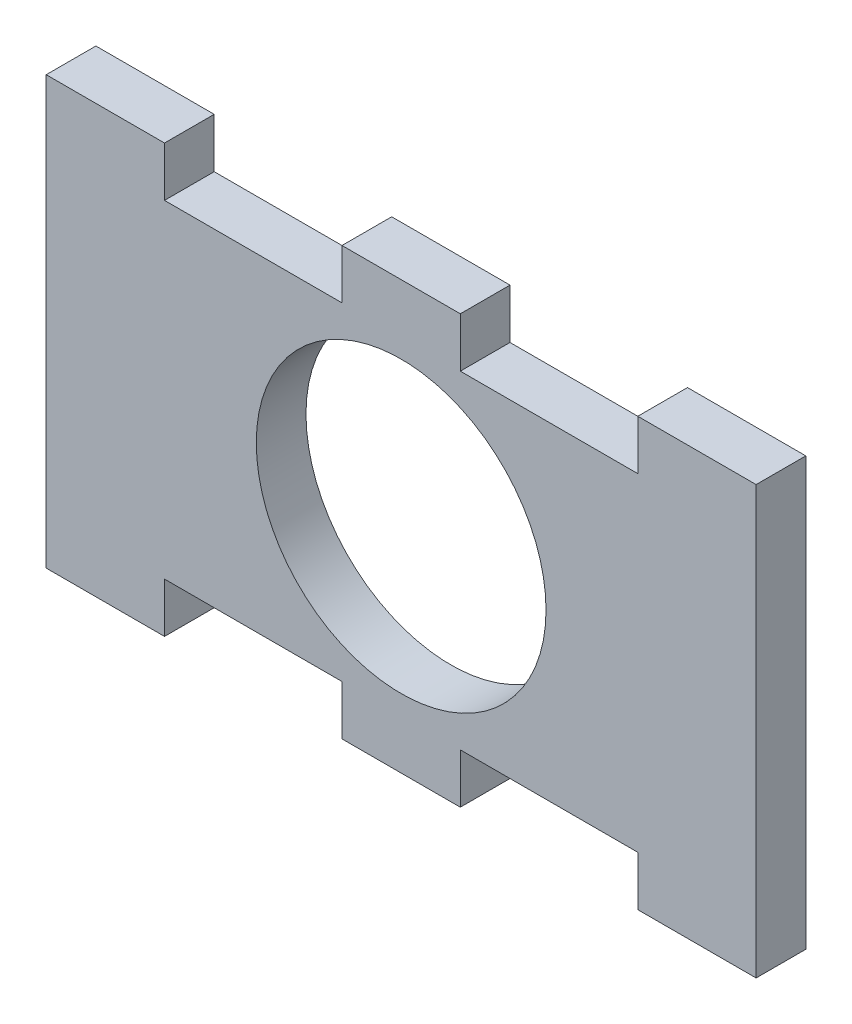
SolidWorks part; units mm, degrees
ref_plane "Front Plane" through (0, 0, 0) normal (0, 0, 1) x (1, 0, 0)
ref_plane "Top Plane" through (0, 0, 0) normal (0, 1, 0) x (1, 0, 0)
ref_plane "Right Plane" through (0, 0, 0) normal (1, 0, 0) x (0, 0, -1)
sketch "Sketch1" plane through (0, 0, 0) normal (0, 0, 1) x (1, 0, 0)
  line L1 (-38.1, 17.6) -> (38.1, 17.6)
  line L2 (-38.1, 17.6) -> (-38.1, -17.6)
  line L3 (-38.1, -17.6) -> (38.1, -17.6)
  line L4 (38.1, 17.6) -> (38.1, -17.6)
  line L5 (-38.1, 17.6) -> (38.1, -17.6) construction
  line L6 (-38.1, -17.6) -> (38.1, 17.6) construction
  point P0 (0, 0)
  dimension "D1" = 35.2
  dimension "D2" = 76.2
extrude "Boss-Extrude1" add sketch "Sketch1" against normal blind 5.334
sketch "Sketch2" plane through (0, 0, 0) normal (0, 0, 1) x (1, 0, 0)
  circle A0 centre (0, 0) radius 15.55
  dimension "D1" = 31.1
extrude "Cut-Extrude1" cut sketch "Sketch2" against normal through all
sketch "Sketch3" plane through (0, 17.6, 0) normal (0, 1, 0) x (1, 0, 0)
  line L0 (0, 14.0499) -> (0, 5.334) construction
  line L1 (38.1, 0) -> (-38.1, 0) construction
  line L2 (-38.1, 5.334) -> (-25.4, 5.334)
  line L3 (-38.1, 5.334) -> (-38.1, 0)
  line L4 (-38.1, 0) -> (-25.4, 0)
  line L5 (-25.4, 5.334) -> (-25.4, 0)
  line L6 (38.1, 5.334) -> (-38.1, 5.334) construction
  line L7 (6.35, 5.334) -> (-6.35, 5.334)
  line L8 (6.35, 5.334) -> (6.35, 0)
  line L9 (6.35, 0) -> (-6.35, 0)
  line L10 (-6.35, 5.334) -> (-6.35, 0)
  line L11 (0, 0) -> (0, -7.65) construction
  line L12 (25.4, 5.334) -> (25.4, 0)
  line L13 (38.1, 0) -> (25.4, 0)
  line L14 (38.1, 5.334) -> (38.1, 0)
  line L15 (38.1, 5.334) -> (25.4, 5.334)
  dimension "D1" = 12.7
  dimension "D2" = 6.35
extrude "Boss-Extrude2" add sketch "Sketch3" along normal blind 5.334
sketch "Sketch4" plane through (0, -17.6, 0) normal (0, -1, 0) x (1, 0, 0)
  line L0 (-38.1, -5.334) -> (38.1, -5.334) construction
  line L1 (-38.1, 0) -> (-25.4, 0)
  line L2 (-38.1, 0) -> (-38.1, -5.334)
  line L3 (-38.1, -5.334) -> (-25.4, -5.334)
  line L4 (-25.4, 0) -> (-25.4, -5.334)
  line L5 (0, 7.8784) -> (0, 0) construction
  line L6 (0, -5.334) -> (0, -11.385) construction
  line L7 (6.35, 0) -> (-6.35, 0)
  line L8 (6.35, 0) -> (6.35, -5.334)
  line L9 (6.35, -5.334) -> (-6.35, -5.334)
  line L10 (-6.35, 0) -> (-6.35, -5.334)
  line L11 (25.4, 0) -> (25.4, -5.334)
  line L12 (38.1, -5.334) -> (25.4, -5.334)
  line L13 (38.1, 0) -> (38.1, -5.334)
  line L14 (38.1, 0) -> (25.4, 0)
  dimension "D1" = 12.7
  dimension "D2" = 6.35
extrude "Boss-Extrude3" add sketch "Sketch4" along normal blind 5.334
